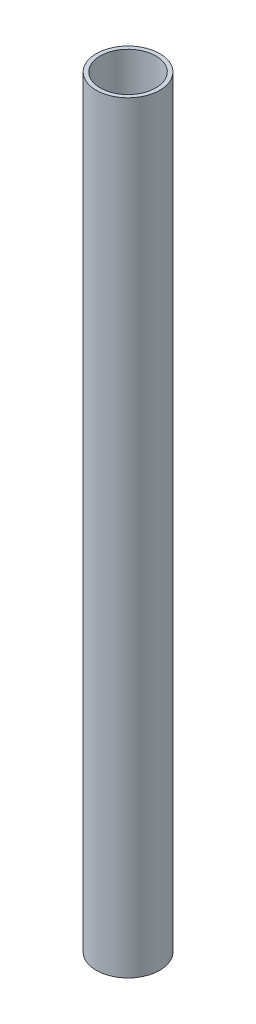
SolidWorks part; units mm, degrees
material "6061-T6 (SS)"
ref_plane "Front Plane" through (0, 0, 0) normal (0, 0, 1) x (1, 0, 0)
ref_plane "Top Plane" through (0, 0, 0) normal (0, 1, 0) x (1, 0, 0)
ref_plane "Right Plane" through (0, 0, 0) normal (1, 0, 0) x (0, 0, -1)
sketch "Sketch1" plane through (0, 0, 0) normal (0, 1, 0) x (1, 0, 0)
  circle A0 centre (0, 0) radius 25.4
  circle A1 centre (0, 0) radius 22.225
  dimension "D1" = 50.8
  dimension "D2" = 3.175
extrude "Boss-Extrude1" add sketch "Sketch1" along normal blind 609.6
